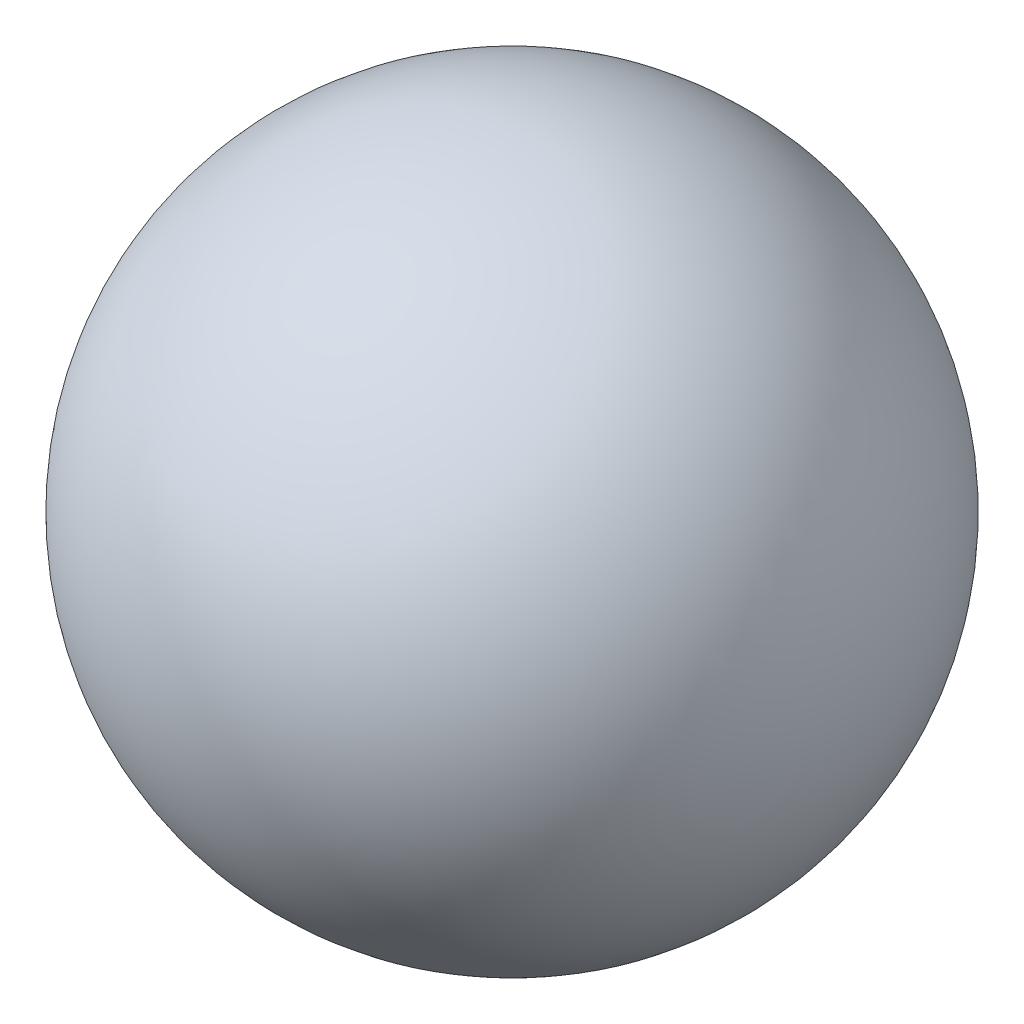
SolidWorks part; units mm, degrees
ref_plane "Front Plane" through (0, 0, 0) normal (0, 0, 1) x (1, 0, 0)
ref_plane "Top Plane" through (0, 0, 0) normal (0, 1, 0) x (1, 0, 0)
ref_plane "Right Plane" through (0, 0, 0) normal (1, 0, 0) x (0, 0, -1)
sketch "Sketch1" plane through (0, 0, 0) normal (0, 0, 1) x (1, 0, 0)
  line L0 (0, 42.4808) -> (0, -42.4808) construction
  line L1 (0, 42.4808) -> (0, -42.4808)
  arc A0 (0, -42.4808) -> (0, 42.4808) centre (0, 0) cw
  point P4 (0, 0)
  point P5 (0, 0)
revolve "Revolve1" add sketch "Sketch1" angle 360 about L0
